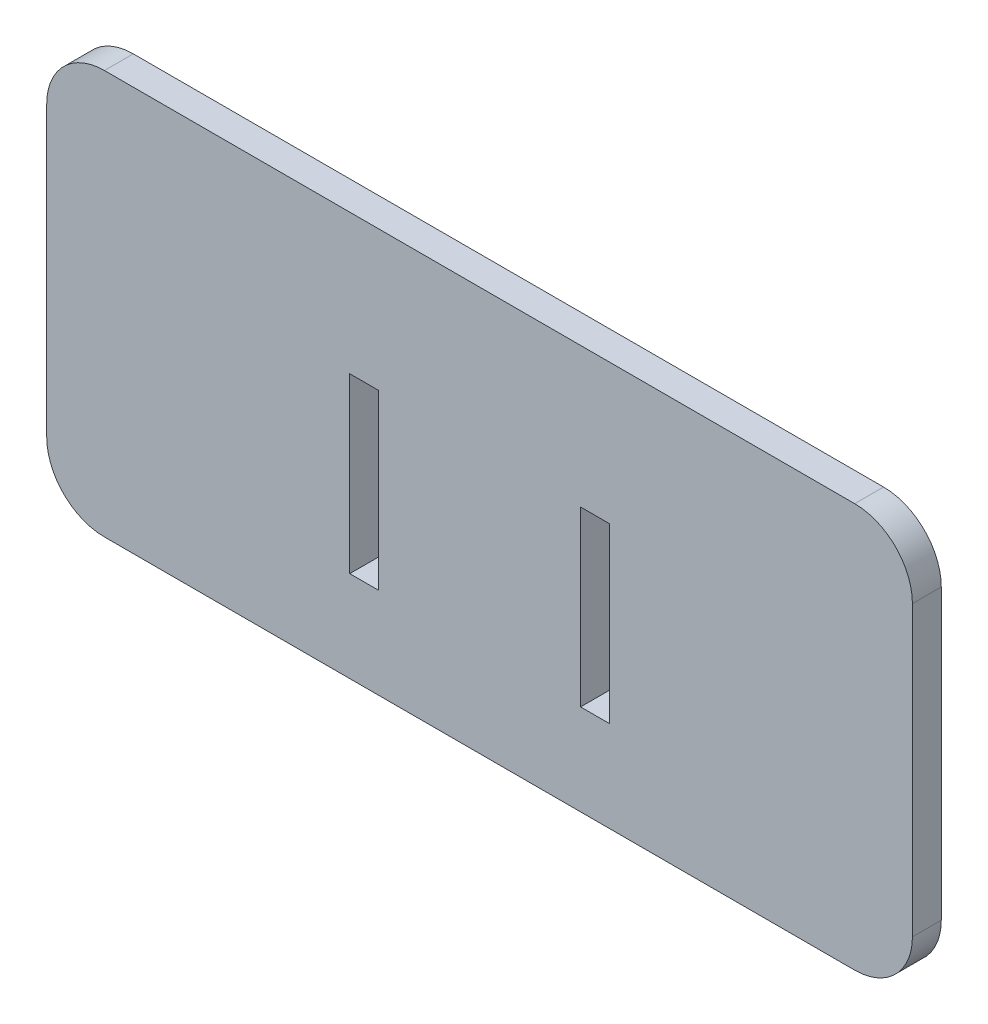
SolidWorks part; units mm, degrees
ref_plane "Front Plane" through (0, 0, 0) normal (0, 0, 1) x (1, 0, 0)
ref_plane "Top Plane" through (0, 0, 0) normal (0, 1, 0) x (1, 0, 0)
ref_plane "Right Plane" through (0, 0, 0) normal (1, 0, 0) x (0, 0, -1)
sketch "Sketch1" plane through (0, 0, 0) normal (0, 0, 1) x (1, 0, 0)
  line L1 (80, 40) -> (-180, 40)
  line L2 (100, 20) -> (100, -80)
  line L3 (80, -100) -> (-180, -100)
  line L4 (-200, 20) -> (-200, -80)
  arc A0 (80, 40) -> (100, 20) centre (80, 20) cw
  arc A1 (100, -80) -> (80, -100) centre (80, -80) cw
  arc A2 (-180, -100) -> (-200, -80) centre (-180, -80) cw
  arc A3 (-180, 40) -> (-200, 20) centre (-180, 20) ccw
  point P0 (0, 0)
  point P10 (100, -100)
  point P13 (-200, -100)
  point P16 (-200, 40)
  dimension "D3" = 20
  dimension "D1" = 300
  dimension "D2" = 140
extrude "Boss-Extrude1" add sketch "Sketch1" along normal blind 10
sketch "Sketch2" plane through (0, 0, 10) normal (0, 0, 1) x (1, 0, 0)
  line L1 (-200, 20) -> (-200, -80) construction
  line L2 (100, -80) -> (100, 20) construction
  line L3 (-90, -38.5) -> (-10, -38.5) construction
  line L4 (-95, -68.5) -> (-85, -68.5)
  line L5 (-95, -68.5) -> (-95, -8.5)
  line L6 (-95, -8.5) -> (-85, -8.5)
  line L7 (-85, -68.5) -> (-85, -8.5)
  line L8 (-95, -68.5) -> (-85, -8.5) construction
  line L9 (-95, -8.5) -> (-85, -68.5) construction
  line L10 (-15, -68.5) -> (-5, -68.5)
  line L11 (-15, -68.5) -> (-15, -8.5)
  line L12 (-15, -8.5) -> (-5, -8.5)
  line L13 (-5, -68.5) -> (-5, -8.5)
  line L14 (-15, -68.5) -> (-5, -8.5) construction
  line L15 (-15, -8.5) -> (-5, -68.5) construction
  line L16 (-200, -38.5) -> (100, -38.5) construction
  point P0 (-200, -30)
  point P6 (-90, -38.5)
  point P11 (-10, -38.5)
  dimension "D1" = 70
  dimension "D2" = 10
  dimension "D3" = 60
  dimension "D4" = 8.5
extrude "Cut-Extrude1" cut sketch "Sketch2" against normal blind 10
